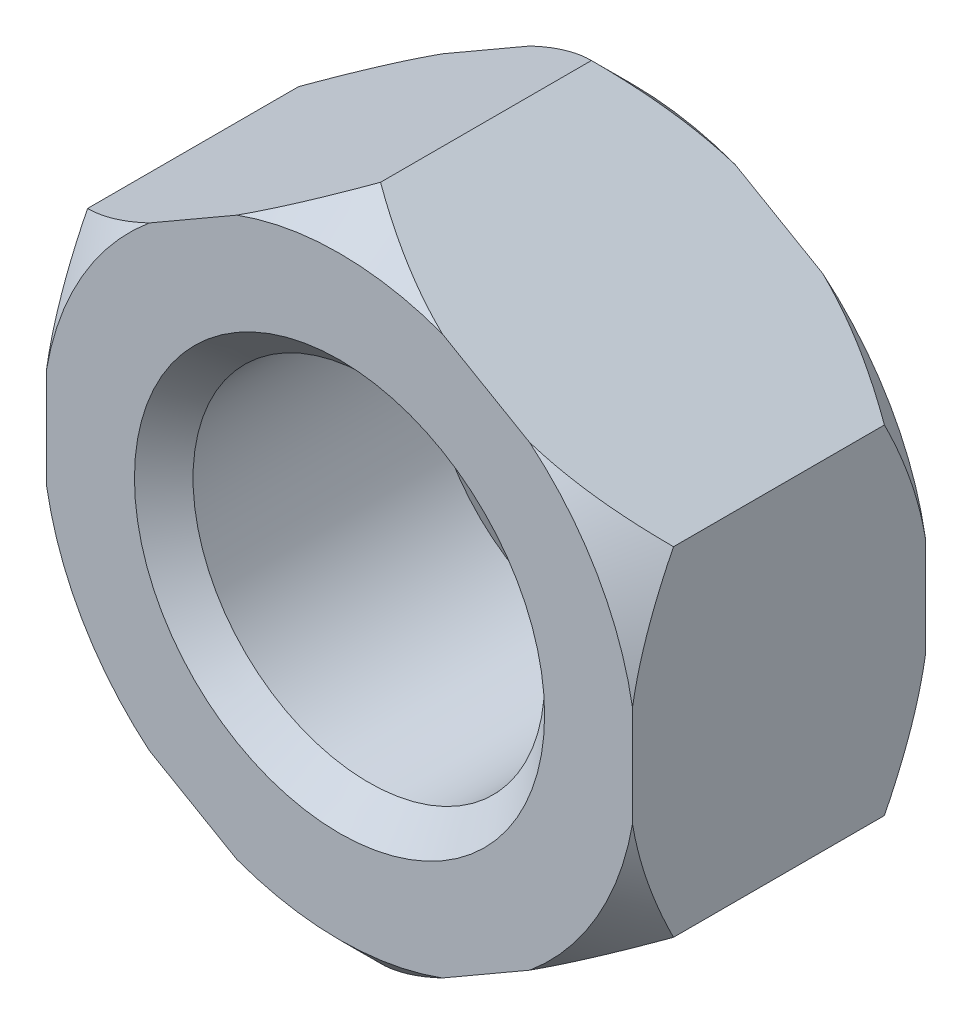
SolidWorks part; units mm, degrees
ref_plane "Спереди" through (0, 0, 0) normal (0, 0, 1) x (1, 0, 0)
ref_plane "Сверху" through (0, 0, 0) normal (0, 1, 0) x (1, 0, 0)
ref_plane "Справа" through (0, 0, 0) normal (1, 0, 0) x (0, 0, -1)
sketch "Эскиз1" plane through (0, 0, 0) normal (0, 0, 1) x (1, 0, 0)
  line L0 (0, 3.7738) -> (0, -4.1898) construction
  line L1 (-3.4469, 0) -> (3.2389, 0) construction
  line L3 (0, 5.7735) -> (-5, 2.8868)
  line L4 (-5, 2.8868) -> (-5, -2.8868)
  line L5 (-5, -2.8868) -> (0, -5.7735)
  line L6 (0, -5.7735) -> (5, -2.8868)
  line L7 (5, -2.8868) -> (5, 2.8868)
  line L8 (5, 2.8868) -> (0, 5.7735)
  circle A0 centre (0, 0) radius 5 construction
extrude "Вытянуть1" add sketch "Эскиз1" along normal blind 5
sketch "Эскиз2" plane through (0, 0, 0) normal (0, 0, -1) x (-1, 0, 0)
  circle A0 centre (0, 0) radius 3
ref_axis "Ось4" through (0, 0, 2.6338) along (0, 0, -1)
sketch "Эскиз15" plane through (0, 0, 0) normal (1, 0, 0) x (0, 0, -1)
  line L0 (-5, 5.7735) -> (-5, 5.0735)
  line L1 (-5, 2.8868) -> (-5, 5.7735) construction
  line L2 (-5, 5.0735) -> (-4.3, 5.7735)
  line L3 (-5, 5.7735) -> (0, 5.7735) construction
  line L4 (-4.3, 5.7735) -> (-5, 5.7735)
  line L5 (-0.7, 5.7735) -> (0, 5.7735)
  line L6 (0, 5.7735) -> (0, 5.0735)
  line L7 (0, 5.0735) -> (-0.7, 5.7735)
revolve "Вырез-Повернуть1" cut sketch "Эскиз15" angle 360 about axis through (0, 0, 2.6338) along (0, 0, -1)
ref_plane "Плоскость1" through (5, 0.8605, 5) normal (-0.1696, 0.9855, 0) x (-0.9855, -0.1696, 0)
extrude "Вырез-Вытянуть1" cut sketch "Эскиз2" against normal through all
chamfer "Фаска1" distance 0.5 angle 45 2 edges at (-3, 0, 0) (-3, 0, 5)
